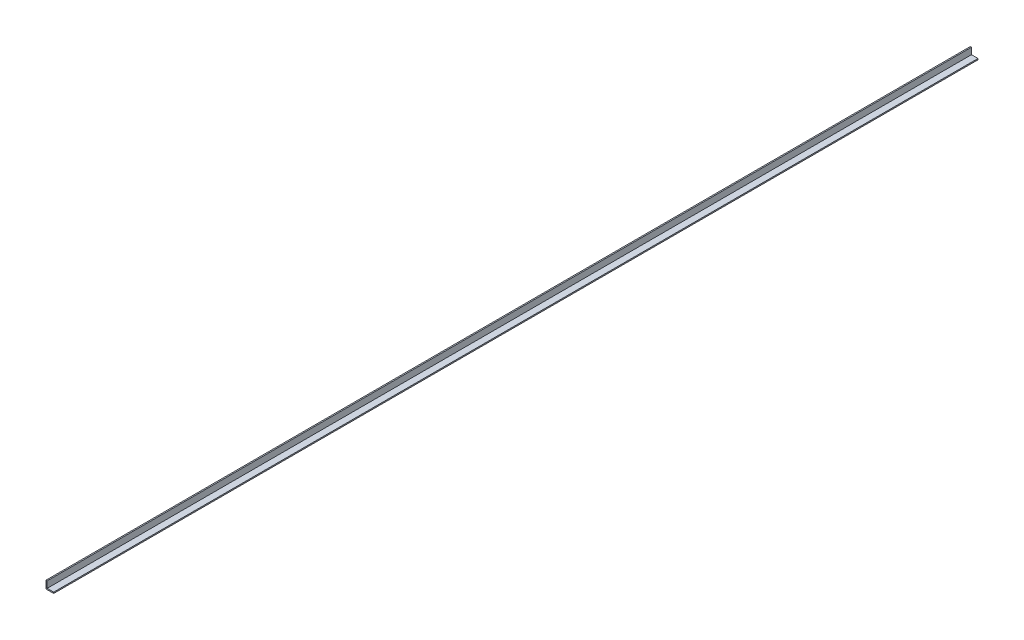
SolidWorks part; units mm, degrees
material "ASTM A36 Acero"
ref_plane "Alzado" through (0, 0, 0) normal (0, 0, 1) x (1, 0, 0)
ref_plane "Planta" through (0, 0, 0) normal (0, 1, 0) x (1, 0, 0)
ref_plane "Vista lateral" through (0, 0, 0) normal (1, 0, 0) x (0, 0, -1)
sketch "Croquis1" plane through (0, 0, 0) normal (0, 0, 1) x (1, 0, 0)
  line L0 (0, 50.8) -> (0, 0)
  line L1 (0, 0) -> (50.8, 0)
  line L2 (50.8, 0) -> (50.8, 7.94)
  line L3 (50.8, 7.94) -> (7.94, 7.94)
  line L4 (7.94, 7.94) -> (7.94, 50.8)
  line L5 (7.94, 50.8) -> (0, 50.8)
  dimension "D1" = 7.94
  dimension "D2" = 50.8
extrude "Saliente-Extruir1" add sketch "Croquis1" against normal blind 6100
